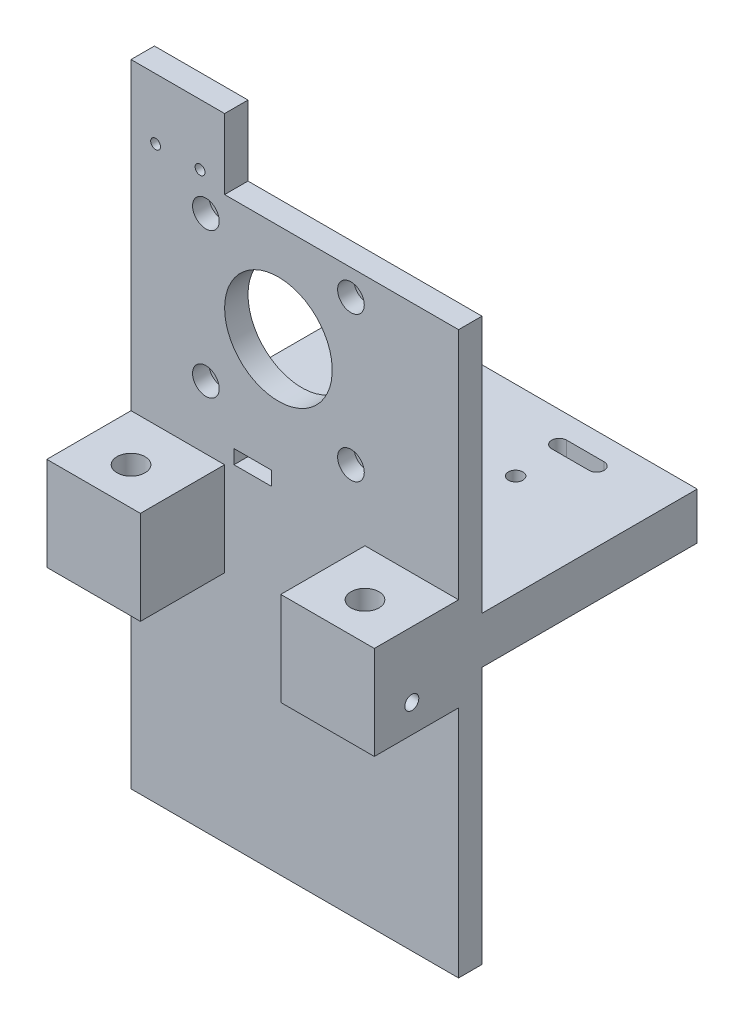
SolidWorks part; units mm, degrees
ref_plane "Front" through (0, 0, 0) normal (0, 0, 1) x (1, 0, 0)
ref_plane "Top" through (0, 0, 0) normal (0, 1, 0) x (1, 0, 0)
ref_plane "Right" through (0, 0, 0) normal (1, 0, 0) x (0, 0, -1)
sketch "Sketch1" plane through (0, 0, 0) normal (0, 0, 1) x (1, 0, 0)
  line L1 (-35, -60) -> (35, -60)
  line L2 (-35, -60) -> (-35, 60)
  line L3 (-35, 60) -> (35, 60)
  line L4 (35, -60) -> (35, 60)
  line L5 (-35, -60) -> (35, 60) construction
  line L6 (-35, 60) -> (35, -60) construction
  point P0 (0, 0)
  dimension "D1" = 120
  dimension "D2" = 70
extrude "Boss-Extrude1" add sketch "Sketch1" along normal blind 5
sketch "Sketch2" plane through (0, 0, 5) normal (0, 0, 1) x (1, 0, 0)
  line L0 (-35, 60) -> (-35, -60) construction
  line L1 (-35, 10) -> (-15, 10)
  line L2 (-35, 10) -> (-35, -10)
  line L3 (-35, -10) -> (-15, -10)
  line L4 (-15, 10) -> (-15, -10)
  line L5 (-35, 10) -> (-15, -10) construction
  line L6 (-35, -10) -> (-15, 10) construction
  line L7 (35, -60) -> (35, 60) construction
  line L8 (35, 10) -> (15, 10)
  line L9 (35, 10) -> (35, -10)
  line L10 (35, -10) -> (15, -10)
  line L11 (15, 10) -> (15, -10)
  line L12 (35, 10) -> (15, -10) construction
  line L13 (35, -10) -> (15, 10) construction
  point P4 (-25, 0)
  point P11 (25, 0)
  dimension "D1" = 20
  dimension "D2" = 20
  dimension "D3" = 20
  dimension "D4" = 20
  dimension "D5" = 10
extrude "Boss-Extrude2" add sketch "Sketch2" along normal blind 18
sketch "Sketch3" plane through (0, 10, 0) normal (0, 1, 0) x (1, 0, 0)
  line L0 (-25, -23) -> (-25, -5) construction
  line L1 (-15, -23) -> (-35, -23) construction
  line L2 (-15, -5) -> (-35, -5) construction
  line L3 (25, -23) -> (25, -5) construction
  line L4 (35, -23) -> (15, -23) construction
  line L5 (35, -5) -> (15, -5) construction
  circle A0 centre (-25, -15) radius 3
  circle A1 centre (25, -15) radius 3
  dimension "D1" = 6
  dimension "D2" = 6
  dimension "D3" = 10
  dimension "D4" = 10
extrude "Cut-Extrude1" cut sketch "Sketch3" against normal up to next
sketch "Sketch4" plane through (0, 0, 0) normal (0, 0, -1) x (-1, 0, 0)
  line L0 (-35, 60) -> (35, 60) construction
  line L1 (-12, 23.5) -> (19, 23.5) construction
  line L2 (-12, 23.5) -> (-12, 54.5) construction
  line L3 (-12, 54.5) -> (19, 54.5) construction
  line L4 (19, 23.5) -> (19, 54.5) construction
  line L5 (-12, 23.5) -> (19, 54.5) construction
  line L6 (-12, 54.5) -> (19, 23.5) construction
  line L7 (35, 60) -> (35, -60) construction
  circle A0 centre (3.5, 39) radius 11.5
  circle A1 centre (-12, 54.5) radius 1.55
  circle A2 centre (19, 54.5) radius 1.55
  circle A3 centre (19, 23.5) radius 1.55
  circle A4 centre (-12, 23.5) radius 1.55
  dimension "D1" = 23
  dimension "D3" = 3.1
  dimension "D4" = 3.1
  dimension "D5" = 3.1
  dimension "D6" = 3.1
  dimension "D2" = 31
  dimension "D7" = 21
  dimension "D8" = 31.5
extrude "Cut-Extrude2" cut sketch "Sketch4" against normal up to next
sketch "Sketch5" plane through (0, 0, 0) normal (0, 0, -1) x (-1, 0, 0)
  line L1 (35, 60) -> (15, 60)
  line L2 (35, 60) -> (35, 75)
  line L3 (35, 75) -> (15, 75)
  line L4 (15, 60) -> (15, 75)
  line L5 (35, 60) -> (15, 75) construction
  line L6 (35, 75) -> (15, 60) construction
  circle A0 centre (20.25, 62) radius 1.05
  circle A1 centre (29.75, 62) radius 1.05
  point P4 (25, 67.5)
  dimension "D3" = 2.1
  dimension "D4" = 2.1
  dimension "D5" = 9.5
  dimension "D7" = 13
  dimension "D1" = 15
  dimension "D2" = 20
  dimension "D6" = 5.25
extrude "Boss-Extrude3" add sketch "Sketch5" against normal up to surface (5 mm away) up to face at (10.45, 23.5, 5)
sketch "Sketch6" plane through (0, 0, 0) normal (0, 0, -1) x (-1, 0, 0)
  line L0 (-35, -60) -> (-35, 60) construction
  line L1 (-35, 5) -> (35, 5)
  line L2 (-35, 5) -> (-35, -5)
  line L3 (-35, -5) -> (35, -5)
  line L4 (35, 5) -> (35, -5)
  line L5 (-35, 5) -> (35, -5) construction
  line L6 (-35, -5) -> (35, 5) construction
  line L7 (35, 75) -> (35, -60) construction
  line L8 (35, -60) -> (-35, -60) construction
  point P4 (0, 0)
  dimension "D1" = 10
  dimension "D2" = 55
extrude "Boss-Extrude4" add sketch "Sketch6" along normal blind 46
sketch "Sketch7" plane through (0, -10, 0) normal (0, 1, 0) x (1, 0, 0)
  line L0 (35, -23) -> (35, -5) construction
  line L1 (29.4, -17.85) -> (32, -17.85)
  line L2 (29.4, -17.85) -> (29.4, -12.15)
  line L3 (29.4, -12.15) -> (32, -12.15)
  line L4 (32, -17.85) -> (32, -12.15)
  line L5 (29.4, -17.85) -> (32, -12.15) construction
  line L6 (29.4, -12.15) -> (32, -17.85) construction
  line L8 (-32, -17.85) -> (-29.4, -17.85)
  line L9 (-32, -17.85) -> (-32, -12.15)
  line L10 (-32, -12.15) -> (-29.4, -12.15)
  line L11 (-29.4, -17.85) -> (-29.4, -12.15)
  line L12 (-32, -17.85) -> (-29.4, -12.15) construction
  line L13 (-32, -12.15) -> (-29.4, -17.85) construction
  line L14 (-35, -23) -> (-35, -5) construction
  line L15 (-25, -15) -> (-30.7, -15) construction
  point P0 (30.7, -15)
  point P5 (-30.7, -15)
  dimension "D1" = 5.7
  dimension "D2" = 2.6
  dimension "D3" = 3
  dimension "D4" = 5.7
  dimension "D5" = 2.6
  dimension "D7" = 3
extrude "Cut-Extrude3" cut sketch "Sketch7" along normal blind 10
sketch "Sketch8" plane through (35, 0, 0) normal (1, 0, 0) x (0, 0, -1)
  line L0 (-23, -10) -> (-23, 10) construction
  line L2 (-23, -10) -> (-5, -10) construction
  circle A0 centre (-15, -4) radius 1.5
  dimension "D1" = 3
  dimension "D3" = 6
  dimension "D2" = 8
extrude "Cut-Extrude4" cut sketch "Sketch8" against normal blind 8
sketch "Sketch9" plane through (-35, 0, 0) normal (-1, 0, 0) x (0, 0, 1)
  circle A0 centre (15, -4) radius 1.5 construction
  circle A1 centre (15, -4) radius 1.5
extrude "Cut-Extrude5" cut sketch "Sketch9" against normal blind 8
sketch "Sketch10" plane through (0, 0, 5) normal (0, 0, 1) x (1, 0, 0)
  circle A0 centre (-19, 54.5) radius 2.85
  circle A1 centre (12, 54.5) radius 2.85
  circle A2 centre (12, 23.5) radius 2.85
  circle A3 centre (-19, 23.5) radius 2.85
  dimension "D1" = 5.7
  dimension "D2" = 5.7
  dimension "D3" = 5.7
  dimension "D4" = 5.7
extrude "Cut-Extrude6" cut sketch "Sketch10" against normal blind 3.5
sketch "Sketch11" plane through (0, 5, 0) normal (0, 1, 0) x (1, 0, 0)
  line L1 (13.194, 4) -> (-11.806, 4) construction
  line L2 (13.194, 4) -> (13.194, 29) construction
  line L3 (13.194, 29) -> (-11.806, 29) construction
  line L4 (-11.806, 4) -> (-11.806, 29) construction
  line L5 (13.194, 4) -> (-11.806, 29) construction
  line L6 (13.194, 29) -> (-11.806, 4) construction
  line L7 (-35, 0) -> (35, 0) construction
  circle A0 centre (-11.806, 29) radius 1.55
  circle A1 centre (-11.806, 4) radius 1.55
  circle A2 centre (13.194, 29) radius 1.55
  circle A3 centre (13.194, 4) radius 1.55
  point P0 (0.694, 16.5)
  dimension "D2" = 3.1
  dimension "D3" = 3.1
  dimension "D4" = 3.1
  dimension "D5" = 3.1
  dimension "D1" = 25
  dimension "D6" = 4
extrude "Cut-Extrude7" cut sketch "Sketch11" against normal up to next
sketch "Sketch13" plane through (0, 5, 0) normal (0, 1, 0) x (1, 0, 0)
  line L0 (-20, 39.5) -> (-12, 39.5) construction
  line L1 (-20, 41.1) -> (-12, 41.1)
  line L2 (-20, 37.9) -> (-12, 37.9)
  line L3 (-35, 46) -> (35, 46) construction
  line L4 (-35, 46) -> (-35, 0) construction
  line L5 (0, 46) -> (0, 39.5) construction
  line L6 (20, 39.5) -> (12, 39.5) construction
  line L7 (20, 41.1) -> (12, 41.1)
  line L8 (20, 37.9) -> (12, 37.9)
  arc A0 (-20, 41.1) -> (-20, 37.9) centre (-20, 39.5) ccw
  arc A1 (-12, 37.9) -> (-12, 41.1) centre (-12, 39.5) ccw
  arc A2 (20, 41.1) -> (20, 37.9) centre (20, 39.5) cw
  arc A3 (12, 37.9) -> (12, 41.1) centre (12, 39.5) cw
  point P2 (-16, 39.5)
  point P16 (16, 39.5)
  dimension "D1" = 1.6
  dimension "D2" = 8
  dimension "D3" = 6.5
  dimension "D4" = 15
extrude "Cut-Extrude8" cut sketch "Sketch13" against normal up to next
sketch "Sketch14" plane through (-35, 0, 0) normal (-1, 0, 0) x (0, 0, 1)
  line L1 (0, -5) -> (-8, -5)
  line L2 (0, -5) -> (0, -21)
  line L3 (0, -21) -> (-8, -21)
  line L4 (-8, -5) -> (-8, -21)
  line L5 (0, -5) -> (-8, -21) construction
  line L6 (0, -21) -> (-8, -5) construction
  point P4 (-4, -13)
  dimension "D1" = 16
  dimension "D2" = 8
extrude "Boss-Extrude5" add sketch "Sketch14" against normal blind 4
sketch "Sketch15" plane through (0, 0, 0) normal (0, 0, -1) x (-1, 0, 0)
  line L0 (35, 5) -> (-35, 5) construction
  line L1 (5, 14) -> (13, 14)
  line L2 (5, 14) -> (5, 11)
  line L3 (5, 11) -> (13, 11)
  line L4 (13, 14) -> (13, 11)
  line L5 (5, 14) -> (13, 11) construction
  line L6 (5, 11) -> (13, 14) construction
  line L7 (35, 75) -> (35, 5) construction
  point P0 (9, 12.5)
  dimension "D1" = 3
  dimension "D2" = 8
  dimension "D3" = 6
  dimension "D4" = 26
extrude "Cut-Extrude9" cut sketch "Sketch15" against normal up to next
